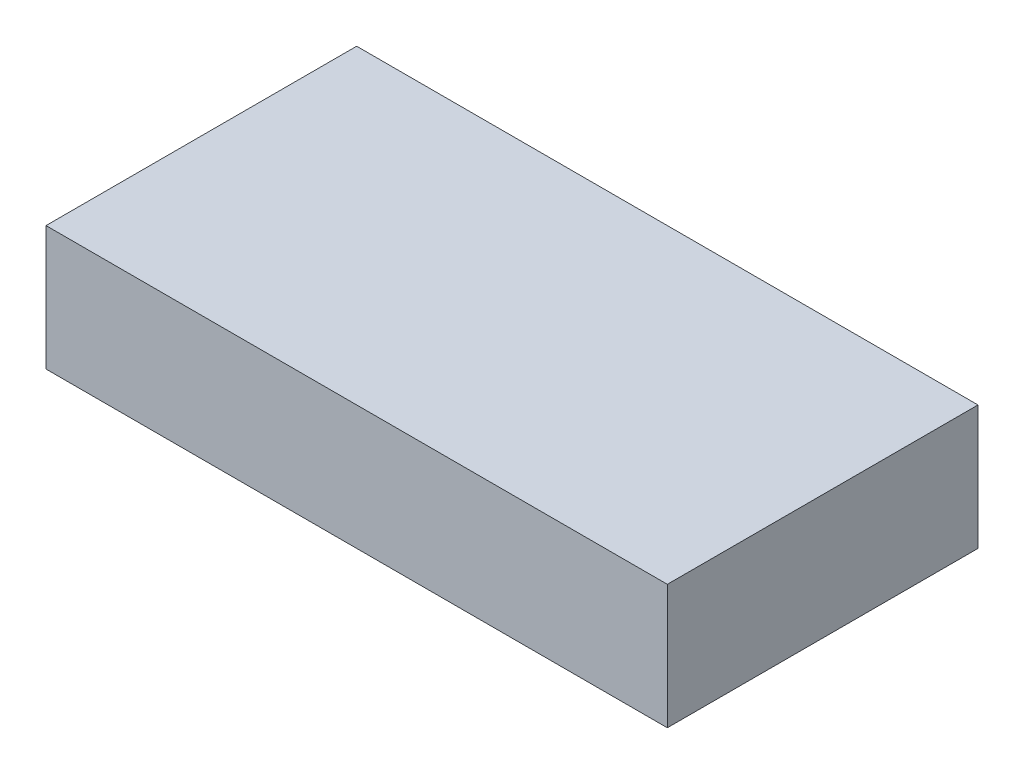
SolidWorks part; units mm, degrees
ref_plane "Спереди" through (0, 0, 0) normal (0, 0, 1) x (1, 0, 0)
ref_plane "Сверху" through (0, 0, 0) normal (0, 1, 0) x (1, 0, 0)
ref_plane "Справа" through (0, 0, 0) normal (1, 0, 0) x (0, 0, -1)
sketch "Эскиз1" plane through (0, 0, 0) normal (0, 1, 0) x (1, 0, 0)
  line L1 (-5, -2.5) -> (5, -2.5)
  line L2 (-5, -2.5) -> (-5, 2.5)
  line L3 (-5, 2.5) -> (5, 2.5)
  line L4 (5, -2.5) -> (5, 2.5)
  line L5 (-5, -2.5) -> (5, 2.5) construction
  line L6 (-5, 2.5) -> (5, -2.5) construction
  point P0 (0, 0)
  dimension "D1" = 10
  dimension "D2" = 5
extrude "Бобышка-Вытянуть1" add sketch "Эскиз1" along normal blind 2
